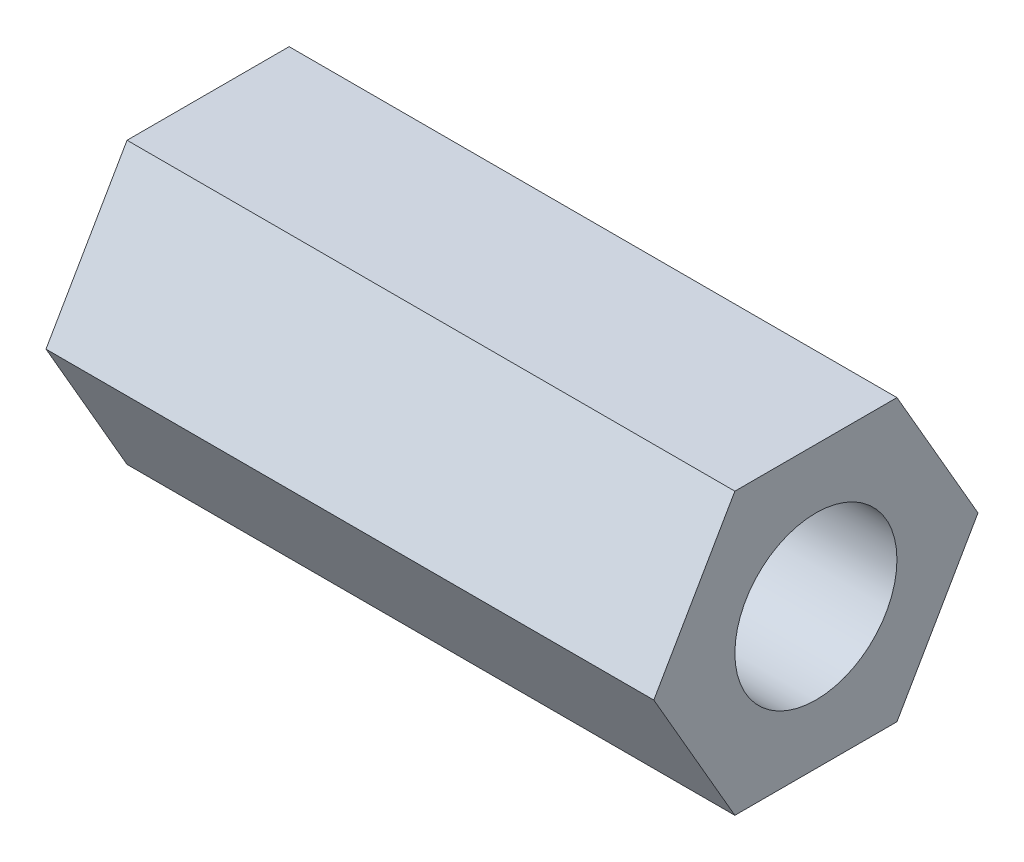
SolidWorks part; units mm, degrees
material "黄铜"
ref_plane "前视基准面" through (0, 0, 0) normal (0, 0, 1) x (1, 0, 0)
ref_plane "上视基准面" through (0, 0, 0) normal (0, 1, 0) x (1, 0, 0)
ref_plane "右视基准面" through (0, 0, 0) normal (1, 0, 0) x (0, 0, -1)
other "Configuration Table"
sketch "草图1" plane through (0, 0, 0) normal (1, 0, 0) x (0, 0, -1)
  line L1 (-4, 0) -> (-2, -3.4641)
  line L2 (-2, -3.4641) -> (2, -3.4641)
  line L3 (2, -3.4641) -> (4, 0)
  line L4 (4, 0) -> (2, 3.4641)
  line L5 (2, 3.4641) -> (-2, 3.4641)
  line L6 (-2, 3.4641) -> (-4, 0)
  circle A0 centre (0, 0) radius 2
  circle A1 centre (0, 0) radius 3.4641 construction
  dimension "D1" = 4
  dimension "D2" = 4
extrude "凸台-拉伸1" add sketch "草图1" along normal blind 15
equation "\"15、\"=10"
